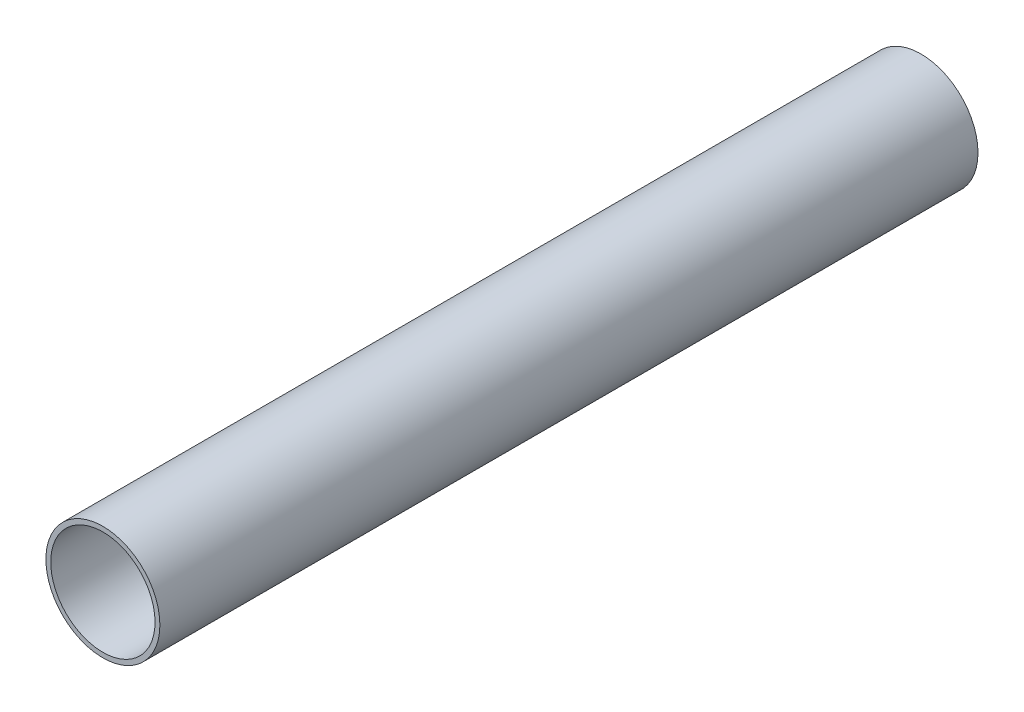
SolidWorks part; units mm, degrees
material "Thornel Mat VMA"
ref_plane "Front Plane" through (0, 0, 0) normal (0, 0, 1) x (1, 0, 0)
ref_plane "Top Plane" through (0, 0, 0) normal (0, 1, 0) x (1, 0, 0)
ref_plane "Right Plane" through (0, 0, 0) normal (1, 0, 0) x (0, 0, -1)
sketch "Sketch1" plane through (0, 0, 0) normal (0, 0, 1) x (1, 0, 0)
  circle A0 centre (0, 0) radius 10.45
  circle A1 centre (0, 0) radius 9.565
  dimension "D1" = 20.9
  dimension "D2" = 19.13
extrude "Boss-Extrude1" add sketch "Sketch1" along normal blind 150
